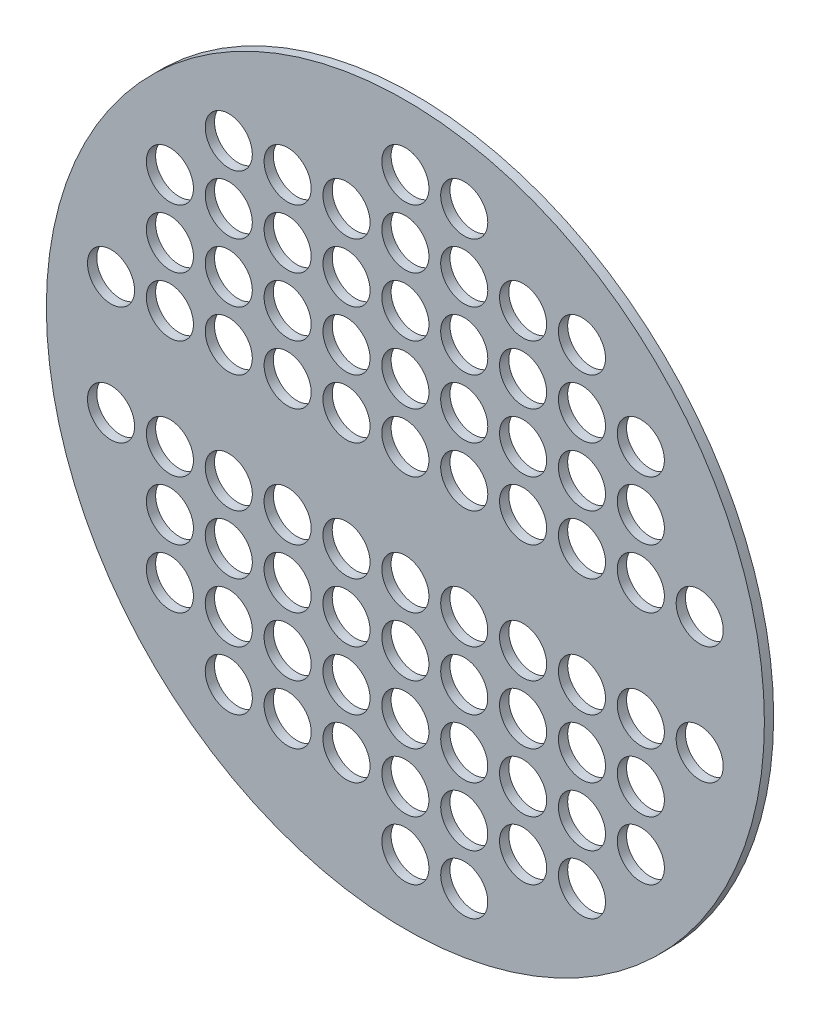
SolidWorks part; units mm, degrees
ref_plane "Front Plane" through (0, 0, 0) normal (0, 0, 1) x (1, 0, 0)
ref_plane "Top Plane" through (0, 0, 0) normal (0, 1, 0) x (1, 0, 0)
ref_plane "Right Plane" through (0, 0, 0) normal (1, 0, 0) x (0, 0, -1)
sketch "Sketch1" plane through (0, 0, 0) normal (0, 0, 1) x (1, 0, 0)
  circle A0 centre (0, 0) radius 193.65
  dimension "D1" = 387.3
extrude "Boss-Extrude1" add sketch "Sketch1" along normal blind 5
sketch "Sketch2" plane through (0, 0, 5) normal (0, 0, 1) x (1, 0, 0)
  line L0 (0, 193.65) -> (0, 0) construction
  line L1 (0, 0) -> (165.6565, 0) construction
  circle A0 centre (0, 0) radius 193.65 construction
  circle A1 centre (0, 158.75) radius 12.7
  circle A2 centre (31.75, 158.75) radius 12.7
  circle A3 centre (-95.25, 127) radius 12.7
  circle A4 centre (-63.5, 127) radius 12.7
  circle A5 centre (-31.75, 127) radius 12.7
  circle A6 centre (0, 127) radius 12.7
  circle A7 centre (31.75, 127) radius 12.7
  circle A8 centre (63.5, 127) radius 12.7
  circle A9 centre (95.25, 127) radius 12.7
  circle A10 centre (-63.5, 95.25) radius 12.7
  circle A11 centre (-31.75, 95.25) radius 12.7
  circle A12 centre (0, 95.25) radius 12.7
  circle A13 centre (31.75, 95.25) radius 12.7
  circle A14 centre (63.5, 95.25) radius 12.7
  circle A15 centre (95.25, 95.25) radius 12.7
  circle A16 centre (-63.5, 63.5) radius 12.7
  circle A17 centre (-31.75, 63.5) radius 12.7
  circle A18 centre (0, 63.5) radius 12.7
  circle A19 centre (31.75, 63.5) radius 12.7
  circle A20 centre (63.5, 63.5) radius 12.7
  circle A21 centre (95.25, 63.5) radius 12.7
  circle A22 centre (-63.5, 31.75) radius 12.7
  circle A23 centre (-31.75, 31.75) radius 12.7
  circle A24 centre (0, 31.75) radius 12.7
  circle A25 centre (31.75, 31.75) radius 12.7
  circle A26 centre (63.5, 31.75) radius 12.7
  circle A27 centre (95.25, 31.75) radius 12.7
  circle A28 centre (-95.25, 95.25) radius 12.7
  circle A29 centre (-95.25, 63.5) radius 12.7
  circle A30 centre (-95.25, 31.75) radius 12.7
  circle A31 centre (-127, 95.25) radius 12.7
  circle A32 centre (-127, 63.5) radius 12.7
  circle A33 centre (-127, 31.75) radius 12.7
  circle A34 centre (-158.75, 31.75) radius 12.7
  circle A35 centre (158.75, 31.75) radius 12.7
  circle A36 centre (127, 31.75) radius 12.7
  circle A37 centre (127, 63.5) radius 12.7
  circle A38 centre (127, 95.25) radius 12.7
  circle A39 centre (127, -95.25) radius 12.7
  circle A40 centre (127, -63.5) radius 12.7
  circle A41 centre (127, -31.75) radius 12.7
  circle A42 centre (158.75, -31.75) radius 12.7
  circle A43 centre (-158.75, -31.75) radius 12.7
  circle A44 centre (-127, -31.75) radius 12.7
  circle A45 centre (-127, -63.5) radius 12.7
  circle A46 centre (-127, -95.25) radius 12.7
  circle A47 centre (-95.25, -31.75) radius 12.7
  circle A48 centre (-95.25, -63.5) radius 12.7
  circle A49 centre (-95.25, -95.25) radius 12.7
  circle A50 centre (95.25, -31.75) radius 12.7
  circle A51 centre (63.5, -31.75) radius 12.7
  circle A52 centre (31.75, -31.75) radius 12.7
  circle A53 centre (0, -31.75) radius 12.7
  circle A54 centre (-31.75, -31.75) radius 12.7
  circle A55 centre (-63.5, -31.75) radius 12.7
  circle A56 centre (95.25, -63.5) radius 12.7
  circle A57 centre (63.5, -63.5) radius 12.7
  circle A58 centre (31.75, -63.5) radius 12.7
  circle A59 centre (0, -63.5) radius 12.7
  circle A60 centre (-31.75, -63.5) radius 12.7
  circle A61 centre (-63.5, -63.5) radius 12.7
  circle A62 centre (95.25, -95.25) radius 12.7
  circle A63 centre (63.5, -95.25) radius 12.7
  circle A64 centre (31.75, -95.25) radius 12.7
  circle A65 centre (0, -95.25) radius 12.7
  circle A66 centre (-31.75, -95.25) radius 12.7
  circle A67 centre (-63.5, -95.25) radius 12.7
  circle A68 centre (95.25, -127) radius 12.7
  circle A69 centre (63.5, -127) radius 12.7
  circle A70 centre (31.75, -127) radius 12.7
  circle A71 centre (0, -127) radius 12.7
  circle A72 centre (-31.75, -127) radius 12.7
  circle A73 centre (-63.5, -127) radius 12.7
  circle A74 centre (-95.25, -127) radius 12.7
  circle A75 centre (31.75, -158.75) radius 12.7
  circle A76 centre (0, -158.75) radius 12.7
  point P74 (0, 0)
  point P75 (0, 0)
  point P76 (0, 0)
  point P77 (-158.75, 33)
  point P78 (-125.7072, 33)
  point P79 (0, 0)
  dimension "D1" = 25.4
  dimension "D2" = 31.75
  dimension "D3" = 31.75
  dimension "D4" = 31.75
  dimension "D7" = 31.75
  dimension "D8" = 31.75
  dimension "D9" = 31.75
  dimension "D10" = 31.75
  dimension "D5" = 7
  dimension "D6" = 4
extrude "Cut-Extrude1" cut sketch "Sketch2" against normal through all
